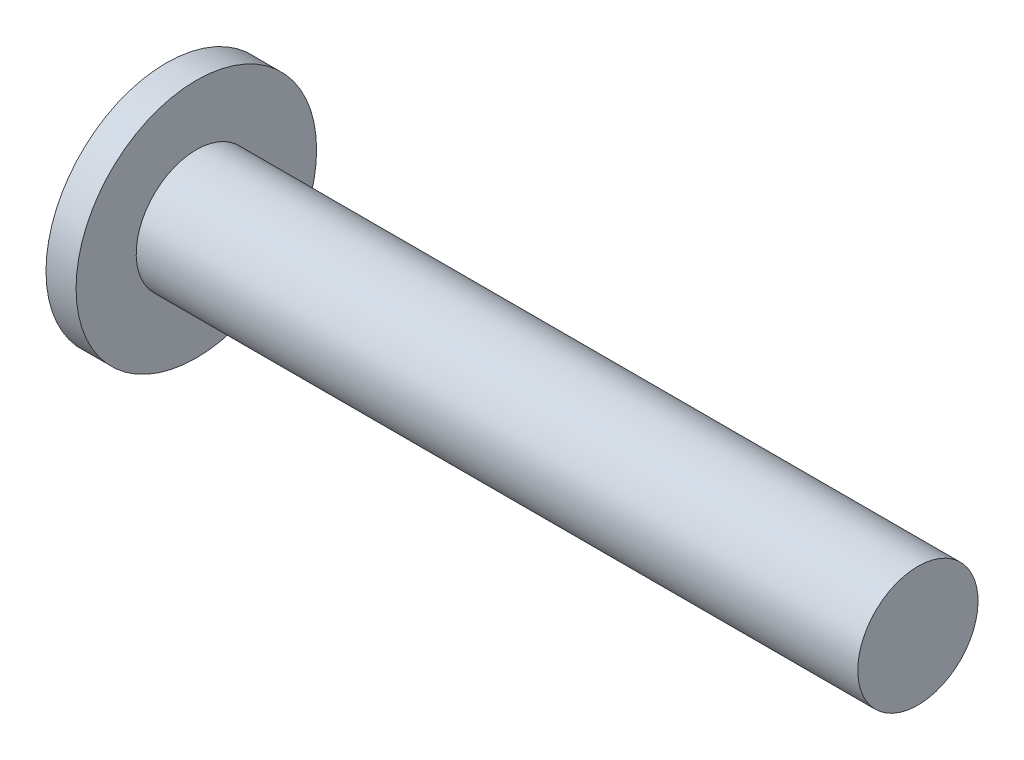
SolidWorks part; units mm, degrees
ref_plane "Front Plane" through (0, 0, 0) normal (0, 0, 1) x (1, 0, 0)
ref_plane "Top Plane" through (0, 0, 0) normal (0, 1, 0) x (1, 0, 0)
ref_plane "Right Plane" through (0, 0, 0) normal (1, 0, 0) x (0, 0, -1)
sketch "Sketch4" plane through (0, 0, 0) normal (0, 0, 1) x (1, 0, 0)
  line L0 (0, 0) -> (0, 40)
  line L1 (0, 40) -> (10, 40)
  line L2 (10, 40) -> (10, 20)
  line L3 (10, 20) -> (250, 20)
  line L4 (250, 20) -> (250, 0)
  line L5 (250, 0) -> (0, 0)
  dimension "D1" = 20
  dimension "D2" = 40
  dimension "D3" = 10
  dimension "D4" = 250
revolve "Revolve1" add sketch "Sketch4" angle 360 about L5
scale "Scale1" scale about centroid uniform scaling yes scale factor 0.35
